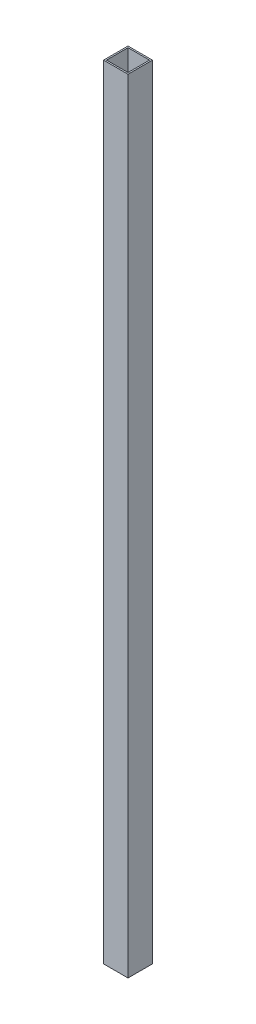
SolidWorks part; units mm, degrees
ref_plane "Front Plane" through (0, 0, 0) normal (0, 0, 1) x (1, 0, 0)
ref_plane "Top Plane" through (0, 0, 0) normal (0, 1, 0) x (1, 0, 0)
ref_plane "Right Plane" through (0, 0, 0) normal (1, 0, 0) x (0, 0, -1)
sketch "Sketch1" plane through (0, 0, 0) normal (0, 1, 0) x (1, 0, 0)
  line L0 (-26.6278, 1.8372) -> (-14.1278, -10.6628) construction
  line L1 (-26.6278, 1.8372) -> (-14.1278, 1.8372)
  line L2 (-26.6278, 1.8372) -> (-26.6278, -10.6628)
  line L3 (-26.6278, -10.6628) -> (-14.1278, -10.6628)
  line L4 (-14.1278, 1.8372) -> (-14.1278, -10.6628)
  line L5 (-26.6278, -10.6628) -> (-14.1278, 1.8372) construction
  line L7 (-25.8778, 1.0872) -> (-14.8778, 1.0872)
  line L8 (-25.8778, 1.0872) -> (-25.8778, -9.9128)
  line L9 (-25.8778, -9.9128) -> (-14.8778, -9.9128)
  line L10 (-14.8778, 1.0872) -> (-14.8778, -9.9128)
  line L11 (-25.8778, 1.0872) -> (-14.8778, -9.9128) construction
  line L12 (-25.8778, -9.9128) -> (-14.8778, 1.0872) construction
  point P4 (-20.3778, -4.4128)
extrude "Boss-Extrude3" add sketch "Sketch1" along normal blind 400
